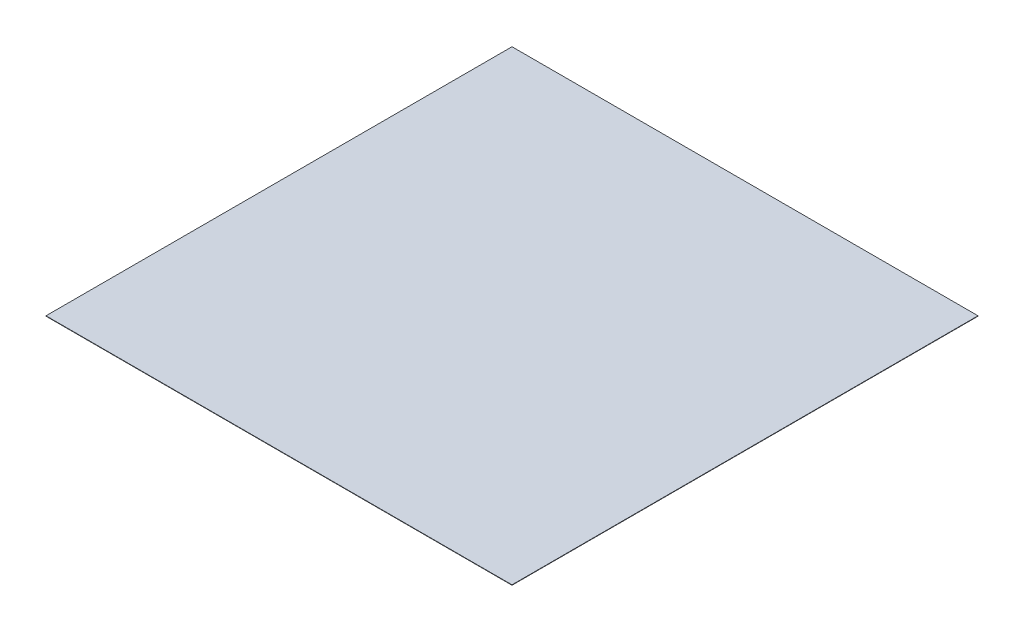
SolidWorks part; units mm, degrees
ref_plane "Front Plane" through (0, 0, 0) normal (0, 0, 1) x (1, 0, 0)
ref_plane "Top Plane" through (0, 0, 0) normal (0, 1, 0) x (1, 0, 0)
ref_plane "Right Plane" through (0, 0, 0) normal (1, 0, 0) x (0, 0, -1)
ref_plane "Plane1" through (0, 0, 134.8832) normal (0, 0, -1) x (-1, 0, 0)
sketch "Sketch2" plane through (0, 0, 134.8832) normal (0, 0, -1) x (-1, 0, 0)
  line L0 (-16.0101, 140.5644) -> (-16.0101, 106.5644)
  line L1 (-16.0101, 140.5644) -> (-16.0101, 106.5644) construction
  line L2 (-23.0101, 103.5644) -> (-19.0101, 103.5644)
  line L3 (-23.0101, 103.5644) -> (-19.0101, 103.5644) construction
  line L4 (-26.0101, 96.5644) -> (-26.0101, 100.5644)
  line L5 (-26.0101, 96.5644) -> (-26.0101, 100.5644) construction
  line L6 (-29.0101, 93.5644) -> (-63.0101, 93.5644)
  line L7 (-29.0101, 93.5644) -> (-63.0101, 93.5644) construction
  line L8 (-76.0101, 106.5644) -> (-76.0101, 140.5644)
  line L9 (-76.0101, 106.5644) -> (-76.0101, 140.5644) construction
  line L10 (-73.0101, 103.5644) -> (-69.0101, 103.5644)
  line L11 (-73.0101, 103.5644) -> (-69.0101, 103.5644) construction
  line L12 (-66.0101, 100.5644) -> (-66.0101, 96.5644)
  line L13 (-66.0101, 100.5644) -> (-66.0101, 96.5644) construction
  line L14 (-63.0101, 153.5644) -> (-29.0101, 153.5644)
  line L15 (-63.0101, 153.5644) -> (-29.0101, 153.5644) construction
  line L16 (-26.0101, 146.5644) -> (-26.0101, 150.5644)
  line L17 (-26.0101, 146.5644) -> (-26.0101, 150.5644) construction
  line L18 (-19.0101, 143.5644) -> (-23.0101, 143.5644)
  line L19 (-19.0101, 143.5644) -> (-23.0101, 143.5644) construction
  line L20 (-69.0101, 143.5644) -> (-73.0101, 143.5644)
  line L21 (-69.0101, 143.5644) -> (-73.0101, 143.5644) construction
  line L22 (-66.0101, 150.5644) -> (-66.0101, 146.5644)
  line L23 (-66.0101, 150.5644) -> (-66.0101, 146.5644) construction
  line L24 (-66.5101, 150.5644) -> (-66.5101, 146.5644)
  line L25 (-69.0101, 144.0644) -> (-73.0101, 144.0644)
  line L26 (-76.5101, 106.5644) -> (-76.5101, 140.5644)
  line L27 (-73.0101, 103.0644) -> (-69.0101, 103.0644)
  line L28 (-66.5101, 100.5644) -> (-66.5101, 96.5644)
  line L29 (-29.0101, 93.0644) -> (-63.0101, 93.0644)
  line L30 (-25.5101, 96.5644) -> (-25.5101, 100.5644)
  line L31 (-23.0101, 103.0644) -> (-19.0101, 103.0644)
  line L32 (-15.5101, 140.5644) -> (-15.5101, 106.5644)
  line L33 (-19.0101, 144.0644) -> (-23.0101, 144.0644)
  line L34 (-25.5101, 146.5644) -> (-25.5101, 150.5644)
  line L36 (-29.0101, 153.5644) -> (-84.0101, 153.5644)
  line L37 (-29.0101, 153.5644) -> (-8.0101, 153.5644)
  line L38 (-84.0101, 106.5644) -> (-84.0101, 140.5644)
  line L39 (-73.9683, 95.6063) -> (-73.9683, 95.6063)
  line L40 (-73.9683, 95.6063) -> (-73.9683, 95.6063)
  line L41 (-29.0101, 85.5644) -> (-63.0101, 85.5644)
  line L42 (-18.0519, 95.6063) -> (-18.0519, 95.6063)
  line L43 (-18.0519, 95.6063) -> (-18.0519, 95.6063)
  line L44 (-8.0101, 140.5644) -> (-8.0101, 106.5644)
  line L48 (-8.0101, 140.5644) -> (-8.0101, 153.5644)
  line L50 (-84.0101, 140.5644) -> (-84.0101, 153.5644)
  line L53 (-18.0519, 151.5226) -> (-18.0519, 151.5226) construction
  line L54 (-18.0519, 151.5226) -> (-18.0519, 151.5226) construction
  line L55 (-73.9683, 151.5226) -> (-73.9683, 151.5226) construction
  line L56 (-73.9683, 151.5226) -> (-73.9683, 151.5226) construction
  line L57 (-63.0101, 154.0644) -> (-29.0101, 154.0644) construction
  line L58 (-63.0101, 161.5644) -> (-29.0101, 161.5644) construction
  arc A0 (-19.0101, 103.5644) -> (-16.0101, 106.5644) centre (-19.0101, 106.5644) ccw
  arc A1 (-19.0101, 103.5644) -> (-16.0101, 106.5644) centre (-19.0101, 106.5644) ccw construction
  arc A2 (-23.0101, 103.5644) -> (-26.0101, 100.5644) centre (-23.0101, 100.5644) ccw
  arc A3 (-23.0101, 103.5644) -> (-26.0101, 100.5644) centre (-23.0101, 100.5644) ccw construction
  arc A4 (-29.0101, 93.5644) -> (-26.0101, 96.5644) centre (-29.0101, 96.5644) ccw
  arc A5 (-29.0101, 93.5644) -> (-26.0101, 96.5644) centre (-29.0101, 96.5644) ccw construction
  arc A6 (-66.0101, 96.5644) -> (-63.0101, 93.5644) centre (-63.0101, 96.5644) ccw
  arc A7 (-66.0101, 96.5644) -> (-63.0101, 93.5644) centre (-63.0101, 96.5644) ccw construction
  arc A8 (-76.0101, 106.5644) -> (-73.0101, 103.5644) centre (-73.0101, 106.5644) ccw
  arc A9 (-76.0101, 106.5644) -> (-73.0101, 103.5644) centre (-73.0101, 106.5644) ccw construction
  arc A10 (-66.0101, 100.5644) -> (-69.0101, 103.5644) centre (-69.0101, 100.5644) ccw
  arc A11 (-66.0101, 100.5644) -> (-69.0101, 103.5644) centre (-69.0101, 100.5644) ccw construction
  arc A12 (-26.0101, 150.5644) -> (-29.0101, 153.5644) centre (-29.0101, 150.5644) ccw
  arc A13 (-26.0101, 150.5644) -> (-29.0101, 153.5644) centre (-29.0101, 150.5644) ccw construction
  arc A14 (-26.0101, 146.5644) -> (-23.0101, 143.5644) centre (-23.0101, 146.5644) ccw
  arc A15 (-26.0101, 146.5644) -> (-23.0101, 143.5644) centre (-23.0101, 146.5644) ccw construction
  arc A16 (-16.0101, 140.5644) -> (-19.0101, 143.5644) centre (-19.0101, 140.5644) ccw
  arc A17 (-16.0101, 140.5644) -> (-19.0101, 143.5644) centre (-19.0101, 140.5644) ccw construction
  arc A18 (-63.0101, 153.5644) -> (-66.0101, 150.5644) centre (-63.0101, 150.5644) ccw
  arc A19 (-63.0101, 153.5644) -> (-66.0101, 150.5644) centre (-63.0101, 150.5644) ccw construction
  arc A20 (-69.0101, 143.5644) -> (-66.0101, 146.5644) centre (-69.0101, 146.5644) ccw
  arc A21 (-69.0101, 143.5644) -> (-66.0101, 146.5644) centre (-69.0101, 146.5644) ccw construction
  arc A22 (-73.0101, 143.5644) -> (-76.0101, 140.5644) centre (-73.0101, 140.5644) ccw
  arc A23 (-73.0101, 143.5644) -> (-76.0101, 140.5644) centre (-73.0101, 140.5644) ccw construction
  arc A24 (-69.0101, 144.0644) -> (-66.5101, 146.5644) centre (-69.0101, 146.5644) ccw
  arc A25 (-73.0101, 144.0644) -> (-76.5101, 140.5644) centre (-73.0101, 140.5644) ccw
  arc A26 (-76.5101, 106.5644) -> (-73.0101, 103.0644) centre (-73.0101, 106.5644) ccw
  arc A27 (-66.5101, 100.5644) -> (-69.0101, 103.0644) centre (-69.0101, 100.5644) ccw
  arc A28 (-66.5101, 96.5644) -> (-63.0101, 93.0644) centre (-63.0101, 96.5644) ccw
  arc A29 (-29.0101, 93.0644) -> (-25.5101, 96.5644) centre (-29.0101, 96.5644) ccw
  arc A30 (-23.0101, 103.0644) -> (-25.5101, 100.5644) centre (-23.0101, 100.5644) ccw
  arc A31 (-19.0101, 103.0644) -> (-15.5101, 106.5644) centre (-19.0101, 106.5644) ccw
  arc A32 (-15.5101, 140.5644) -> (-19.0101, 144.0644) centre (-19.0101, 140.5644) ccw
  arc A33 (-25.5101, 146.5644) -> (-23.0101, 144.0644) centre (-23.0101, 146.5644) ccw
  arc A34 (-25.5101, 150.5644) -> (-27.2073, 153.5644) centre (-29.0101, 150.5644) ccw
  arc A35 (-64.8129, 153.5644) -> (-66.5101, 150.5644) centre (-63.0101, 150.5644) ccw
  arc A37 (-63.0101, 154.0644) -> (-66.5101, 150.5644) centre (-63.0101, 150.5644) ccw construction
  arc A38 (-84.0101, 106.5644) -> (-73.9683, 95.6063) centre (-73.0101, 106.5644) ccw
  arc A39 (-73.9683, 95.6063) -> (-73.9683, 95.6063) centre (-73.9683, 95.6063) ccw
  arc A40 (-73.9683, 95.6063) -> (-63.0101, 85.5644) centre (-63.0101, 96.5644) ccw
  arc A41 (-29.0101, 85.5644) -> (-18.0519, 95.6063) centre (-29.0101, 96.5644) ccw
  arc A42 (-18.0519, 95.6063) -> (-18.0519, 95.6063) centre (-18.0519, 95.6063) ccw
  arc A43 (-18.0519, 95.6063) -> (-8.0101, 106.5644) centre (-19.0101, 106.5644) ccw
  arc A44 (-25.5101, 150.5644) -> (-29.0101, 154.0644) centre (-29.0101, 150.5644) ccw construction
  arc A49 (-8.0101, 140.5644) -> (-18.0519, 151.5226) centre (-19.0101, 140.5644) ccw construction
  arc A50 (-18.0519, 151.5226) -> (-29.0101, 161.5644) centre (-29.0101, 150.5644) ccw construction
  arc A51 (-63.0101, 161.5644) -> (-73.9683, 151.5226) centre (-63.0101, 150.5644) ccw construction
  arc A52 (-73.9683, 151.5226) -> (-84.0101, 140.5644) centre (-73.0101, 140.5644) ccw construction
  arc A53 (-18.0519, 151.5226) -> (-18.0519, 151.5226) centre (-18.0519, 151.5226) ccw construction
  arc A54 (-73.9683, 151.5226) -> (-73.9683, 151.5226) centre (-73.9683, 151.5226) ccw construction
  dimension "D1" = 0.5
  dimension "D2" = 8
extrude "Boss-Extrude1" add sketch "Sketch2" along normal blind 20 contours A41 A43 L44 L48 L37 A34 L34 A33 L33 A32 L32 A31 L31 A30 L30 A29 L29 A28 L28 A27 L27 A26 L26 A25 L25 A24 L24 A35 L36 L50 L38 A38 A40 L41
ref_plane "Plane2" through (0, 153.5644, 0) normal (0, 1, 0) x (1, 0, 0)
sketch "Sketch3" plane through (0, 153.5644, 0) normal (0, 1, 0) x (1, 0, 0)
  line L1 (-1.9899, -144.8832) -> (24.2073, -144.8832)
  line L2 (-1.9899, -144.8832) -> (-1.9899, -104.8832)
  line L3 (-1.9899, -104.8832) -> (24.2073, -104.8832)
  line L4 (98.0101, -144.8832) -> (98.0101, -104.8832)
  line L5 (67.8129, -104.8832) -> (67.8129, -144.8832)
  line L7 (24.2073, -104.8832) -> (24.2073, -144.8832)
  line L9 (48.0101, -104.8832) -> (48.0101, -144.8832) construction
  line L10 (98.0101, -124.8832) -> (-1.9899, -124.8832) construction
  line L13 (67.8129, -104.8832) -> (98.0101, -104.8832)
  line L14 (67.8129, -144.8832) -> (98.0101, -144.8832)
  circle A0 centre (93.0101, -109.8832) radius 1.5
  circle A1 centre (93.0101, -139.8832) radius 1.5
  circle A2 centre (3.0101, -139.8832) radius 1.5
  circle A3 centre (3.0101, -109.8832) radius 1.5
  dimension "D5" = 67.8129
  dimension "D1" = 3
  dimension "D2" = 3.0101
  dimension "D3" = 24.2073
  dimension "D4" = 48.0101
  dimension "D6" = 93.0101
  dimension "D7" = 98.0101
  dimension "D8" = 1.9899
  dimension "D9" = 104.8832
  dimension "D10" = 109.8832
  dimension "D11" = 124.8832
  dimension "D12" = 139.8832
extrude "Boss-Extrude2" add sketch "Sketch3" along normal blind 5 from offset 5 offset against normal yes
ref_plane "Plane3" through (0, 201.7644, 0) normal (0, 1, 0) x (1, 0, 0)
sketch "Sketch4" plane through (0, 201.7644, 0) normal (0, 1, 0) x (1, 0, 0)
  line L0 (0, 0) -> (0, 600) construction
  line L1 (600, 600) -> (-600, 600)
  line L2 (600, 600) -> (600, -600)
  line L3 (600, -600) -> (-600, -600)
  line L4 (-600, 600) -> (-600, -600)
  line L5 (0, 0) -> (600, 0) construction
  dimension "D1" = 1200
  dimension "D2" = 1200
  dimension "D3" = 600
  dimension "D4" = 600
extrude "Boss-Extrude3" add sketch "Sketch4" along normal blind 1 separate body
